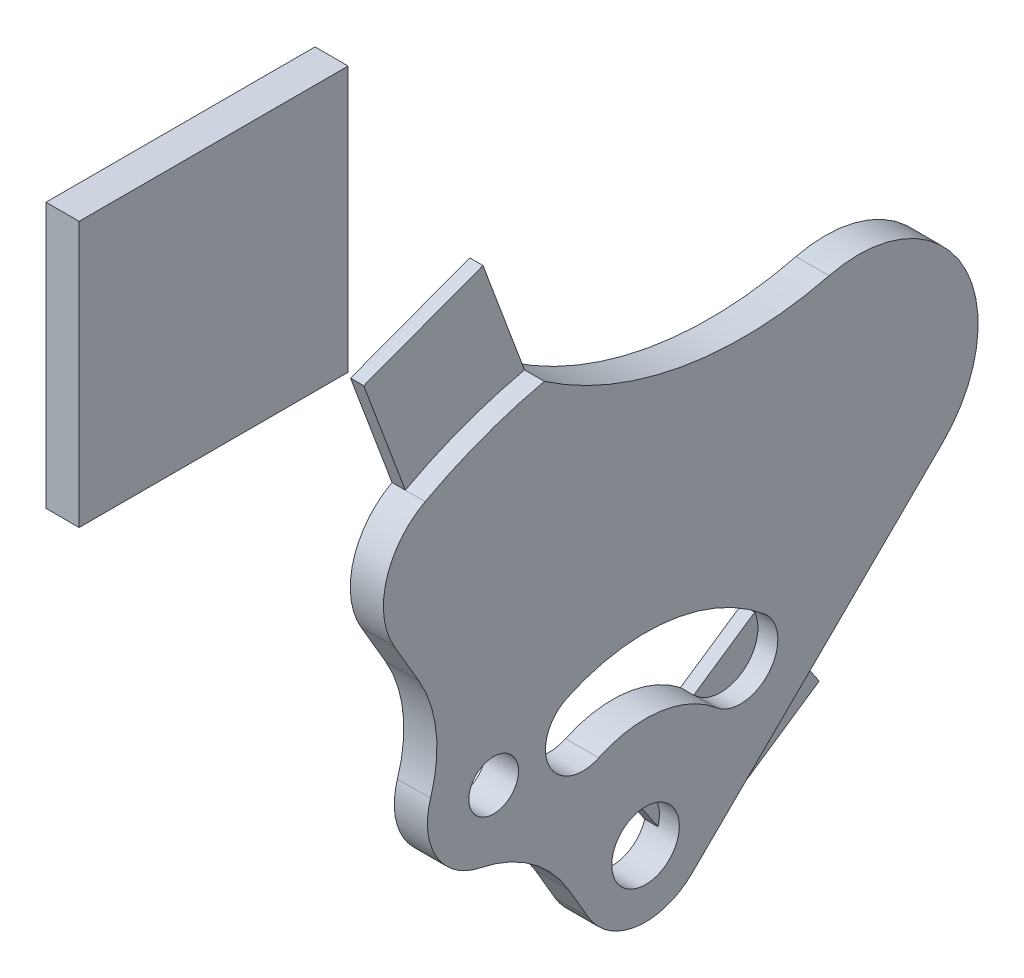
SolidWorks part; units mm, degrees
material "PC High Viscosity"
ref_plane "Front Plane" through (0, 0, 0) normal (0, 0, 1) x (1, 0, 0)
ref_plane "Top Plane" through (0, 0, 0) normal (0, 1, 0) x (1, 0, 0)
ref_plane "Right Plane" through (0, 0, 0) normal (1, 0, 0) x (0, 0, -1)
sketch "Sketch4" plane through (0, 0, 0) normal (1, 0, 0) x (0, 0, -1)
  line L0 (-2.9914, -1.0639) -> (-130.6611, 357.9089) construction
  line L1 (2.9914, 1.0639) -> (-124.6782, 360.0367) construction
  line L2 (-124.6782, 360.0367) -> (-130.6611, 357.9089) construction
  line L3 (-130.6611, 357.9089) -> (-133.6525, 356.845) construction
  line L4 (-133.6525, 356.845) -> (-184.7204, 500.4341) construction
  line L5 (-184.7204, 500.4341) -> (-172.7547, 504.6897) construction
  line L6 (-172.7547, 504.6897) -> (-121.6868, 361.1006) construction
  line L7 (-121.6868, 361.1006) -> (-124.6782, 360.0367) construction
  line L16 (-186.8468, 405.2616) -> (-158.2054, 369.0306)
  line L25 (-177.3558, 422.8765) -> (-158.2054, 369.0306) construction
  line L28 (-159.4072, 429.26) -> (-140.2567, 375.4141) construction
  line L29 (-140.2567, 375.4141) -> (-158.2054, 369.0306) construction
  line L30 (-177.3558, 422.8765) -> (-159.4072, 429.26) construction
  line L32 (32.4045, -6.3458) -> (174.3086, 718.2843) construction
  line L33 (174.3086, 718.2843) -> (227.2775, 707.9114) construction
  line L34 (227.2775, 707.9114) -> (85.3734, -16.7186) construction
  line L35 (85.3734, -16.7186) -> (32.4045, -6.3458) construction
  line L36 (0, 0) -> (32.4045, -6.3458) construction
  line L37 (-674.4124, -1612.5949) -> (1608.6068, -1612.5949) construction
  line L42 (-403.8007, 406.7051) -> (-222.8257, 406.7051) construction
  line L43 (-197.4257, 432.1051) -> (-403.8007, 432.1051) construction
  line L44 (-197.4257, 432.1051) -> (-197.4257, 381.3051) construction
  line L45 (-197.4257, 381.3051) -> (-403.8007, 381.3051) construction
  line L46 (-403.8007, 432.1051) -> (-403.8007, 381.3051) construction
  line L47 (-222.8257, 406.7051) -> (-222.8257, 432.1051) construction
  line L48 (-222.8257, 406.7051) -> (-222.8257, 381.3051) construction
  line L49 (-222.8257, 406.7051) -> (-197.4257, 406.7051) construction
  line L50 (-403.8007, 381.3051) -> (-403.8007, -1612.5949) construction
  line L51 (-251.4007, -1612.5949) -> (-251.4007, -1434.7949) construction
  line L52 (-251.4007, -1434.7949) -> (-168.8507, -1434.7949) construction
  line L53 (-168.8507, -1434.7949) -> (-168.8507, -1612.5949) construction
  line L54 (-186.8468, 405.2616) -> (-172.8601, 410.236) construction
  line L55 (-177.3558, 422.8765) -> (-175.6535, 418.0902)
  line L56 (-175.6535, 418.0902) -> (-157.7049, 424.4737)
  line L57 (-157.7049, 424.4737) -> (-140.2567, 375.4141)
  line L58 (-181.6115, 434.8423) -> (-163.6628, 441.2258) construction
  line L59 (-163.6628, 441.2258) -> (-131.2987, 452.7362) construction
  line L60 (-131.2987, 452.7362) -> (26.3813, 9.3826) construction
  line L61 (26.3813, 9.3826) -> (2.9914, 1.0639) construction
  line L63 (-186.8468, 405.2616) -> (-198.9147, 420.5273)
  line L65 (-246.6871, 397.9992) -> (-226.2306, 341.9309)
  line L66 (-237.676, 336.5464) -> (-264.4742, 382.3241)
  line L67 (-223.6051, 0) -> (0, 0) construction
  line L68 (0, 0) -> (0, 470.5586) construction
  line L70 (-158.2054, 369.0306) -> (-140.2567, 375.4141)
  circle A0 centre (0, 0) radius 3.175 construction
  arc A2 (-246.6871, 397.9992) -> (-222.8257, 432.1051) centre (-222.8257, 406.7051) cw
  arc A17 (-222.8257, 432.1051) -> (-198.9147, 420.5273) centre (-222.8257, 401.6251) cw
  arc A19 (-264.4742, 382.3241) -> (-177.3558, 422.8765) centre (-222.8257, 406.7051) cw
  circle A20 centre (-222.8257, 406.7051) radius 25.4 construction
  circle A21 centre (-222.8257, 411.0231) radius 21.082 construction
  arc A23 (-226.2306, 341.9309) -> (-237.676, 336.5464) centre (-232.196, 339.7544) cw
  circle A24 centre (-232.196, 339.7544) radius 44.45 construction
  dimension "D1" = 6.35
  dimension "D9" = 5.08
  dimension "D10" = 5.08
  dimension "D13" = 11.08
  dimension "D19" = 2044.7
  dimension "D18" = 50.8
  dimension "D7" = 42.164
  dimension "D5" = 57.15
  dimension "D17" = 1612.5949
  dimension "D20" = 50.8
  dimension "D22" = 82.55
  dimension "D23" = 177.8
  dimension "D24" = 152.4
  dimension "D25" = 251.4007
  dimension "D6" = 69.85
  dimension "D27" = 31.75
  dimension "D12" = 19.05
  dimension "D8" = 48.26
  dimension "D11" = 17.78
  dimension "D26" = 6.35
  dimension "D16" = 6.35
  dimension "D2" = 152.4
  dimension "D3" = 12.7
  dimension "D4" = 381
  dimension "D14" = 33.02
  dimension "D15" = 53.975
  dimension "D21" = 206.375
extrude "Boss-Extrude2" add sketch "Sketch4" along normal mid plane 38.1
sketch "Sketch5" plane through (0, 377.5419, 134.2738) normal (0, -0.9422, -0.3351) x (-1, 0, 0)
  line L0 (-19.05, -6.35) -> (-9.525, -6.35) construction
  line L9 (-19.05, -6.35) -> (19.05, -6.35) construction
  line L10 (-9.525, -6.35) -> (9.525, -6.35) construction
  line L11 (9.525, -6.35) -> (19.05, -6.35) construction
  line L12 (-19.05, -25.4) -> (-19.05, -6.35) construction
  line L13 (19.05, -25.4) -> (19.05, -6.35) construction
  line L15 (-19.05, -25.4) -> (-8.89, -19.05)
  line L18 (19.05, -25.4) -> (19.05, -6.35) construction
  line L28 (8.89, -19.05) -> (19.05, -25.4)
  line L30 (-19.05, -46.4997) -> (-19.05, -25.4) construction
  line L32 (-19.05, -25.4) -> (-19.05, -6.35)
  line L33 (-19.05, -6.35) -> (19.05, -6.35)
  line L34 (19.05, -6.35) -> (19.05, -25.4)
  line L39 (-8.89, -19.05) -> (8.89, -19.05)
  circle A0 centre (-9.525, -6.35) radius 3.175 construction
  circle A1 centre (9.525, -6.35) radius 3.175 construction
  dimension "D2" = 12.7
  dimension "D3" = 6.35
  dimension "D1" = 19.05
  dimension "D4" = 17.78
  dimension "D5" = 6.35
  dimension "D6" = 19.05
sketch "Sketch9" plane through (0, 426.6015, 151.722) normal (0, 0.9422, 0.3351) x (1, 0, 0)
  line L0 (0, -6.35) -> (0, -25.4) construction
  line L1 (19.05, -6.35) -> (-19.05, -6.35) construction
  line L2 (19.05, -25.4) -> (-19.05, -25.4) construction
  line L4 (8.89, -19.05) -> (-8.89, -19.05) construction
  circle A0 centre (6.35, -19.05) radius 3.2385
  circle A1 centre (-9.525, -6.35) radius 3.175
  circle A4 centre (9.525, -6.35) radius 3.175
  circle A6 centre (9.525, -6.35) radius 3.175 construction
  circle A7 centre (-9.525, -6.35) radius 3.175 construction
  dimension "D1" = 6.477
  dimension "D2" = 6.35
extrude "Cut-Extrude4" cut sketch "Sketch9" against normal through all
sketch "Sketch12" plane through (19.05, 0, 0) normal (1, 0, 0) x (0, 0, -1)
  line L0 (-233.8882, 379.4995) -> (-227.7504, 377.8715) construction
  line L1 (-238.1338, 369.0584) -> (-227.7504, 377.8715) construction
  line L2 (-236.9571, 380.3135) -> (-233.8882, 379.4995) construction
  line L3 (-233.8882, 379.4995) -> (-230.8193, 378.6855) construction
  circle A2 centre (-230.8193, 378.6855) radius 1.5875
  circle A5 centre (-227.7504, 377.8715) radius 1.5875 construction
  circle A6 centre (-233.8882, 379.4995) radius 1.5875 construction
  circle A7 centre (-236.9571, 380.3135) radius 1.5875
  dimension "D1" = 3.175
  dimension "D4" = 13.6193
extrude "Cut-Extrude5" [suppressed] cut sketch "Sketch12" against normal through all
sketch "Sketch29" plane through (19.05, 0, 0) normal (1, 0, 0) x (0, 0, -1)
  line L0 (-250.3738, 382.2602) -> (-232.196, 339.7544) construction
  line L1 (-246.6871, 397.9992) -> (-226.2306, 341.9309) construction
  line L2 (-237.676, 336.5464) -> (-264.4742, 382.3241) construction
  line L3 (-237.676, 336.5464) -> (-264.4742, 382.3241)
  line L4 (-246.6871, 397.9992) -> (-226.2306, 341.9309)
  arc A1 (-241.8244, 389.8465) -> (-258.9232, 374.6739) centre (-250.3738, 382.2602) ccw
  arc A3 (-177.3558, 422.8765) -> (-264.4742, 382.3241) centre (-222.8257, 406.7051) ccw construction
  arc A4 (-237.676, 336.5464) -> (-226.2306, 341.9309) centre (-232.196, 339.7544) ccw construction
  arc A5 (-222.8257, 432.1051) -> (-246.6871, 397.9992) centre (-222.8257, 406.7051) ccw construction
  arc A6 (-258.9232, 374.6739) -> (-264.4742, 382.3241) centre (-222.8257, 406.7051) ccw
  arc A7 (-241.8244, 389.8465) -> (-246.6871, 397.9992) centre (-222.8257, 406.7051) ccw
  circle A8 centre (-250.3738, 382.2602) radius 3.175 construction
  arc A9 (-237.676, 336.5464) -> (-226.2306, 341.9309) centre (-232.196, 339.7544) ccw
  dimension "D1" = 46.2296
  dimension "D2" = 6.35
sketch "Sketch15" plane through (0, 426.6015, 151.722) normal (0, 0.9422, 0.3351) x (1, 0, 0)
  line L5 (-3.175, -9.392) -> (-3.175, -9.525) construction
  line L6 (-3.175, -9.525) -> (6.35, -9.525)
  line L7 (6.35, -9.525) -> (6.35, -6.35) construction
  line L9 (9.525, -6.35) -> (9.525, -9.525)
  line L10 (9.525, -9.525) -> (6.35, -9.525)
  line L11 (-3.175, -9.525) -> (-9.525, -9.525)
  line L12 (-9.525, -9.525) -> (-9.525, -6.35)
  line L13 (-9.525, -6.35) -> (9.525, -6.35)
  circle A0 centre (9.525, -6.35) radius 3.175 construction
  circle A1 centre (9.525, -6.35) radius 3.175 construction
extrude "Cut-Extrude7" cut sketch "Sketch15" against normal up to surface (52.07 mm away) up to face at (6.35, 370.0733, 155.2737)
sketch "Sketch16" plane through (0, 426.6015, 151.722) normal (0, 0.9422, 0.3351) x (1, 0, 0)
  line L0 (19.05, -6.35) -> (19.05, -25.4) construction
  line L1 (12.7, -6.35) -> (19.05, -6.35)
  line L2 (12.7, -6.35) -> (12.7, 3.175)
  line L3 (12.7, 3.175) -> (19.05, 3.175)
  line L4 (19.05, -6.35) -> (19.05, 3.175)
  line L6 (-19.05, -6.35) -> (-12.7, -6.35)
  line L7 (-19.05, -6.35) -> (-19.05, 3.175)
  line L8 (-19.05, 3.175) -> (-12.7, 3.175)
  line L9 (-12.7, -6.35) -> (-12.7, 3.175)
  dimension "D1" = 9.525
extrude "Boss-Extrude3" add sketch "Sketch16" against normal up to surface (52.07 mm away) up to face at (6.35, 370.0733, 155.2737)
sketch "Sketch20" plane through (19.05, 0, 0) normal (1, 0, 0) x (0, 0, -1)
  line L1 (-148.7306, 427.6655) -> (-175.6535, 418.0902)
  line L2 (-177.3558, 422.8765) -> (-175.6535, 418.0902)
  line L3 (-227.0055, 454.7837) -> (-160.4336, 460.5713)
  line L4 (-160.4336, 460.5713) -> (-148.7306, 427.6655)
  line L5 (-131.2824, 378.6059) -> (-148.7306, 427.6655) construction
  line L6 (-170.2399, 459.7188) -> (-157.7049, 424.4737) construction
  arc A0 (-177.3558, 422.8765) -> (-264.4742, 382.3241) centre (-222.8257, 406.7051) ccw construction
  arc A2 (-227.0055, 454.7837) -> (-177.3558, 422.8765) centre (-222.8257, 406.7051) cw
  dimension "D1" = 9.525
  dimension "D2" = 34.925
extrude "Boss-Extrude5" add sketch "Sketch20" against normal up to surface (38.1 mm away) up to face at (-19.05, 398.1168, 201.4005)
sketch "Sketch21" plane through (0, 426.6015, 151.722) normal (0, -0.9422, -0.3351) x (1, 0, 0)
  line L2 (-19.05, -3.175) -> (-19.05, 25.4) construction
  line L4 (19.05, 14.478) -> (19.05, 6.35)
  line L12 (0, 19.05) -> (0, 6.35) construction
  line L13 (0, 6.35) -> (9.525, 6.35) construction
  line L14 (-9.525, 6.35) -> (0, 6.35) construction
  line L16 (19.05, 6.35) -> (19.05, -3.175)
  line L18 (-19.05, 6.35) -> (-19.05, -3.175)
  line L19 (-19.05, -3.175) -> (-12.7, -3.175) construction
  line L20 (7.62, 24.765) -> (15.3353, 14.478) construction
  line L21 (15.9703, 14.478) -> (19.05, 14.478)
  line L26 (-19.05, -3.175) -> (19.05, -3.175)
  line L27 (-19.05, 14.478) -> (-19.05, 6.35)
  line L28 (0, 19.05) -> (6.35, 19.05) construction
  line L29 (-7.62, 24.765) -> (-15.3353, 14.478) construction
  line L30 (-15.9703, 14.478) -> (-19.05, 14.478)
  line L31 (-14.491, 14.478) -> (14.491, 14.478) construction
  line L32 (8.0264, 25.0698) -> (15.9703, 14.478)
  line L33 (19.05, 25.4) -> (19.05, -3.175) construction
  line L34 (-8.0264, 25.0698) -> (-15.9703, 14.478)
  arc A0 (7.62, 24.765) -> (-7.62, 24.765) centre (0, 19.05) ccw construction
  circle A1 centre (9.525, 6.35) radius 3.175 construction
  circle A2 centre (-9.525, 6.35) radius 3.175 construction
  circle A4 centre (9.525, 6.35) radius 9.525 construction
  circle A5 centre (-9.525, 6.35) radius 9.525 construction
  arc A6 (14.491, 14.478) -> (19.05, 6.35) centre (9.525, 6.35) cw construction
  arc A7 (-14.491, 14.478) -> (-19.05, 6.35) centre (-9.525, 6.35) ccw construction
  circle A10 centre (0, 19.05) radius 10.033 construction
  circle A11 centre (6.35, 19.05) radius 3.2385 construction
  circle A12 centre (6.35, 19.05) radius 3.2385 construction
  arc A13 (-8.0264, 25.0698) -> (8.0264, 25.0698) centre (0, 19.05) cw
  dimension "D1" = 9.525
  dimension "D2" = 12.7
  dimension "D4" = 38.1
  dimension "D5" = 17.653
  dimension "D6" = 6.35
  dimension "D7" = 0.508
  dimension "D3" = 9.525
extrude "Cut-Extrude10" cut sketch "Sketch21" against normal through all
sketch "Sketch22" plane through (19.05, 0, 0) normal (1, 0, 0) x (0, 0, -1)
  line L0 (-250.3738, 382.2602) -> (-253.0021, 402.4135) construction
  line L1 (-253.0021, 402.4135) -> (-248.3687, 390.0742) construction
  line L2 (-239.4905, 381.1842) -> (-219.7422, 376.3814) construction
  circle A3 centre (-250.3738, 382.2602) radius 3.175 construction
  circle A5 centre (-250.3738, 382.2602) radius 3.175 construction
  circle A6 centre (-253.0021, 402.4135) radius 3.175
  arc A7 (-251.0294, 388.3418) -> (-256.1454, 401.9664) centre (-222.8257, 406.7051) ccw construction
  arc A8 (-247.999, 384.3675) -> (-256.1454, 401.9664) centre (-222.8257, 406.7051) ccw construction
  arc A9 (-241.8244, 389.8465) -> (-246.6871, 397.9992) centre (-222.8257, 406.7051) ccw construction
  circle A10 centre (-253.0021, 402.4135) radius 3.175 construction
  circle A11 centre (-248.3687, 390.0742) radius 3.175 construction
  arc A12 (-256.1454, 401.9664) -> (-251.0294, 388.3418) centre (-222.8257, 406.7051) ccw construction
  arc A13 (-256.1454, 401.9664) -> (-251.0294, 388.3418) centre (-222.8257, 406.7051) ccw construction
  circle A14 centre (-239.4905, 381.1842) radius 3.175
  circle A15 centre (-219.7422, 376.3814) radius 3.175 construction
  arc A16 (-241.2264, 378.5257) -> (-219.421, 373.2227) centre (-222.8257, 406.7051) ccw construction
  arc A17 (-241.2264, 378.5257) -> (-219.421, 373.2227) centre (-222.8257, 406.7051) ccw construction
  dimension "D2" = 2.54
extrude "Cut-Extrude11" cut sketch "Sketch22" against normal through all
sketch "Sketch27" plane through (-17.1704, -4.3152, 12.1333) normal (0.8, 0.2011, -0.5653) x (-0.5432, -0.1573, -0.8247)
  line L0 (-201.4256, 405.6346) -> (-205.4694, 414.2586) construction
  line L1 (-223.978, 441.7649) -> (-206.025, 403.4779) construction
  line L3 (-196.8261, 407.7913) -> (-200.2757, 406.1738) construction
  line L4 (-210.0688, 412.1019) -> (-205.4694, 414.2586) construction
  line L6 (-205.4694, 414.2586) -> (-198.0815, 417.7228) construction
  line L7 (-210.8186, 444.8862) -> (-194.0377, 409.0988) construction
  line L8 (-200.2757, 406.1738) -> (-213.0622, 400.1781) construction
  circle A0 centre (-205.4694, 414.2586) radius 6.35
  dimension "D1" = 12.7
  dimension "D2" = 9.525
  dimension "D3" = 5.08
extrude "Cut-Extrude13" cut sketch "Sketch27" against normal blind 5.08 and the other way blind 3.175
sketch "Sketch28" plane through (0, -4.8514, 13.641) normal (0, 0.3351, -0.9422) x (-1, 0, 0)
  line L1 (-19.05, 484.5286) -> (-6.35, 484.5286)
  line L2 (-19.05, 484.5286) -> (-19.05, 478.1786)
  line L3 (-19.05, 478.1786) -> (-6.35, 478.1786)
  line L4 (-6.35, 484.5286) -> (-6.35, 478.1786)
  line L5 (-12.7, 452.7786) -> (-19.05, 452.7786) construction
  line L9 (-19.05, 492.305) -> (-19.05, 452.7786) construction
  dimension "D1" = 12.7
  dimension "D2" = 31.75
  dimension "D3" = 6.35
extrude "Cut-Extrude14" cut sketch "Sketch28" against normal blind 6.35
sketch "Sketch30" plane through (0, 1.0639, -2.9914) normal (0, 0.3351, -0.9422) x (-1, 0, 0)
  line L0 (12.7, 400.7086) -> (12.7, 452.7786) construction
  line L1 (-19.05, 443.2536) -> (-12.7, 443.2536)
  line L2 (-19.05, 443.2536) -> (-19.05, 422.9336)
  line L3 (-19.05, 422.9336) -> (-12.7, 422.9336)
  line L4 (-12.7, 443.2536) -> (-12.7, 422.9336)
  line L6 (-12.7, 400.7086) -> (-19.05, 400.7086) construction
  line L8 (12.7, 443.2536) -> (19.05, 443.2536)
  line L9 (12.7, 443.2536) -> (12.7, 422.9336)
  line L10 (12.7, 422.9336) -> (19.05, 422.9336)
  line L11 (19.05, 443.2536) -> (19.05, 422.9336)
  line L12 (19.05, 452.7786) -> (12.7, 452.7786) construction
  line L13 (-12.7, 400.7086) -> (-12.7, 452.7786) construction
  line L14 (-12.7, 452.7786) -> (-12.7, 400.7086) construction
  dimension "D1" = 6.35
  dimension "D2" = 22.225
  dimension "D4" = 9.525
sketch "Sketch31" plane through (-19.05, 0, 0) normal (-1, 0, 0) x (0, 0, 1)
  line L0 (145.5388, 418.6911) -> (138.7298, 399.5459) construction
  line L1 (177.6708, 403.8935) -> (195.3097, 377.494) construction
  line L2 (170.6506, 380.1104) -> (186.4902, 390.6938) construction
  line L4 (165.363, 421.7501) -> (148.7306, 427.6655) construction
  line L5 (174.479, 394.9192) -> (177.6708, 403.8935) construction
  line L6 (177.6708, 403.8935) -> (154.3219, 412.1976) construction
  line L8 (198.9147, 420.5273) -> (158.2054, 369.0306) construction
  circle A0 centre (177.6708, 403.8935) radius 3.175
  circle A1 centre (174.479, 394.9192) radius 3.175 construction
  circle A2 centre (226.7616, 415.3788) radius 15.875 construction
  arc A5 (246.6871, 397.9992) -> (222.8257, 432.1051) centre (222.8257, 406.7051) ccw construction
  circle A6 centre (177.6708, 403.8935) radius 8.5635 construction
  circle A7 centre (195.3097, 377.494) radius 3.175 construction
  circle A8 centre (195.3097, 377.494) radius 6.35 construction
  circle A9 centre (170.6506, 380.1104) radius 2.7249 construction
  dimension "D1" = 9.525
  dimension "D2" = 3.175
  dimension "D3" = 6.35
  dimension "D5" = 31.75
  dimension "D4" = 12.7
  dimension "D6" = 6.35
  dimension "D8" = 19.05
  dimension "D7" = 31.75
  dimension "D9" = 12.7
sketch "Sketch33" plane through (0, 0, 0) normal (1, 0, 0) x (0, 0, -1)
  line L0 (-199.2473, 457.1969) -> (-212.0786, 429.7194)
  line L1 (-212.0786, 429.7194) -> (-222.8257, 406.7051) construction
  line L3 (-222.8257, 406.7051) -> (-227.0055, 454.7837) construction
  line L4 (-227.0055, 454.7837) -> (-199.2473, 457.1969)
  line L5 (-178.6079, 458.9913) -> (-227.0055, 454.7837) construction
  line L9 (-237.676, 336.5464) -> (-264.4742, 382.3241) construction
  line L10 (-237.676, 336.5464) -> (-264.4742, 382.3241)
  line L11 (-246.6871, 397.9992) -> (-226.2306, 341.9309) construction
  line L12 (-246.6871, 397.9992) -> (-226.2306, 341.9309)
  arc A0 (-227.0055, 454.7837) -> (-264.4742, 382.3241) centre (-222.8257, 406.7051) ccw construction
  arc A1 (-222.8257, 432.1051) -> (-246.6871, 397.9992) centre (-222.8257, 406.7051) ccw construction
  arc A2 (-212.0786, 429.7194) -> (-246.6871, 397.9992) centre (-222.8257, 406.7051) ccw
  arc A3 (-227.0055, 454.7837) -> (-264.4742, 382.3241) centre (-222.8257, 406.7051) ccw
  arc A6 (-237.676, 336.5464) -> (-226.2306, 341.9309) centre (-232.196, 339.7544) ccw construction
  arc A7 (-237.676, 336.5464) -> (-226.2306, 341.9309) centre (-232.196, 339.7544) ccw
  dimension "D1" = 30
extrude "Cut-Extrude18" cut sketch "Sketch33" against normal mid plane 50.8
sketch "Sketch48" plane through (0, 377.5419, 134.2738) normal (0, -0.9422, -0.3351) x (1, 0, 0)
  line L0 (9.525, 9.525) -> (-9.525, 9.525) construction
  line L1 (-2.3813, 55.5406) -> (2.3812, 55.5406)
  line L2 (-2.3813, 55.5406) -> (-2.3812, 9.525)
  line L3 (-2.3812, 9.525) -> (2.3812, 9.525)
  line L4 (2.3812, 55.5406) -> (2.3812, 9.525)
  line L8 (19.05, 55.5406) -> (-19.05, 55.5406) construction
  line L10 (0, 9.525) -> (0, 0) construction
  dimension "D1" = 4.7625
extrude "Cut-Extrude23" cut sketch "Sketch48" against normal up to surface (102.2996 mm away)
sketch "Sketch35" plane through (0, 0, 0) normal (1, 0, 0) x (0, 0, -1)
  line L0 (-202.4062, 450.4323) -> (-212.0786, 429.7194) construction
  line L1 (-212.0786, 429.7194) -> (-222.8257, 406.7051) construction
  line L3 (-178.6079, 458.9913) -> (-199.2473, 457.1969) construction
  line L4 (-204.6452, 456.7277) -> (-202.4062, 450.4323) construction
  line L5 (-178.6079, 458.9913) -> (-176.0021, 451.6645) construction
  line L6 (-199.2473, 457.1969) -> (-211.9088, 430.083) construction
  line L7 (-237.676, 336.5464) -> (-264.4742, 382.3241) construction
  line L8 (-237.676, 336.5464) -> (-264.4742, 382.3241)
  line L9 (-198.9147, 420.5273) -> (-178.0852, 361.9603) construction
  line L10 (-204.6452, 456.7277) -> (-195.7642, 457.4997)
  line L11 (-246.6871, 397.9992) -> (-226.2306, 341.9309)
  line L13 (-204.6452, 456.7277) -> (-195.7642, 457.4997) construction
  line L17 (-198.9147, 420.5273) -> (-158.2054, 369.0306) construction
  line L18 (-198.9147, 420.5273) -> (-189.0698, 408.0736)
  line L21 (-178.0852, 361.9603) -> (-158.2054, 369.0306) construction
  line L22 (-199.2473, 457.1969) -> (-193.349, 457.7097) construction
  line L24 (-158.2054, 369.0306) -> (-143.2482, 374.3502) construction
  line L25 (-187.4365, 446.9653) -> (-172.2286, 427.7275)
  line L27 (-226.0532, 454.857) -> (-204.6452, 456.7277)
  line L28 (-195.7642, 457.4997) -> (-187.4365, 446.9653)
  line L31 (-198.9147, 420.5273) -> (-158.2054, 369.0306) construction
  line L32 (-198.9147, 420.5273) -> (-226.0532, 454.857) construction
  line L34 (-189.0698, 408.0736) -> (-172.2286, 427.7275)
  line L35 (-172.2286, 427.7275) -> (-192.1545, 411.9757) construction
  arc A0 (-177.3558, 422.8765) -> (-264.4742, 382.3241) centre (-222.8257, 406.7051) ccw construction
  arc A2 (-222.8257, 432.1051) -> (-246.6871, 397.9992) centre (-222.8257, 406.7051) ccw construction
  arc A8 (-226.0532, 454.857) -> (-264.4742, 382.3241) centre (-222.8257, 406.7051) ccw
  arc A16 (-237.676, 336.5464) -> (-226.2306, 341.9309) centre (-232.196, 339.7544) ccw construction
  arc A17 (-237.676, 336.5464) -> (-226.2306, 341.9309) centre (-232.196, 339.7544) ccw
  arc A18 (-198.9147, 420.5273) -> (-222.8257, 432.1051) centre (-222.8257, 401.6251) ccw construction
  arc A19 (-198.9147, 420.5273) -> (-222.8257, 432.1051) centre (-222.8257, 401.6251) ccw
  arc A20 (-222.8257, 432.1051) -> (-246.6871, 397.9992) centre (-222.8257, 406.7051) ccw
  dimension "D1" = 25.4
  dimension "D2" = 15.875
  dimension "D3" = 11.08
extrude "Boss-Extrude6" add sketch "Sketch35" along normal mid plane 4.7625 separate body
sketch "Sketch41" plane through (2.3813, 0, 0) normal (1, 0, 0) x (0, 0, -1)
  line L0 (-259.9018, 374.5134) -> (-237.676, 336.5464)
  line L5 (-232.196, 339.7544) -> (-222.8257, 411.0231) construction
  line L6 (-238.2055, 352.5203) -> (-223.0908, 350.5331) construction
  line L7 (-246.3049, 339.6051) -> (-238.2055, 352.5203) construction
  line L8 (-223.0908, 350.5331) -> (-213.5213, 349.2749) construction
  line L9 (-238.2055, 352.5203) -> (-233.0776, 360.6973) construction
  line L10 (-246.6871, 397.9992) -> (-226.2306, 341.9309) construction
  line L13 (-227.7336, 335.2367) -> (-203.7343, 358.942)
  line L14 (-264.4742, 382.3241) -> (-237.676, 336.5464) construction
  line L17 (-198.9147, 420.5273) -> (-158.2054, 369.0306) construction
  arc A0 (-238.2055, 352.5203) -> (-223.0908, 350.5331) centre (-232.196, 339.7544) cw construction
  circle A3 centre (-232.196, 339.7544) radius 44.45 construction
  arc A13 (-237.676, 336.5464) -> (-227.7336, 335.2367) centre (-232.196, 339.7544) ccw
  arc A16 (-237.676, 336.5464) -> (-226.2306, 341.9309) centre (-232.196, 339.7544) ccw construction
  arc A23 (-220.783, 353.2651) -> (-239.7287, 355.7561) centre (-232.196, 339.7544) ccw
  arc A24 (-241.89, 383.1344) -> (-214.6031, 378.257) centre (-222.8257, 411.0231) ccw
  arc A25 (-225.3987, 347.8011) -> (-236.6823, 349.2846) centre (-232.196, 339.7544) ccw
  arc A26 (-222.8257, 432.1051) -> (-246.6871, 397.9992) centre (-222.8257, 406.7051) ccw construction
  arc A27 (-241.89, 383.1344) -> (-259.9018, 374.5134) centre (-232.196, 339.7544) ccw construction
  arc A28 (-225.3987, 347.8011) -> (-220.783, 353.2651) centre (-223.0908, 350.5331) ccw
  arc A29 (-239.7287, 355.7561) -> (-236.6823, 349.2846) centre (-238.2055, 352.5203) ccw
  arc A30 (-238.2055, 352.5203) -> (-246.3049, 339.6051) centre (-232.196, 339.7544) ccw construction
  arc A31 (-239.7287, 355.7561) -> (-249.881, 339.5673) centre (-232.196, 339.7544) ccw construction
  arc A32 (-236.6823, 349.2846) -> (-242.7288, 339.643) centre (-232.196, 339.7544) ccw construction
  arc A33 (-236.6823, 349.2846) -> (-239.7287, 355.7561) centre (-238.2055, 352.5203) ccw construction
  arc A34 (-249.881, 339.5673) -> (-242.7288, 339.643) centre (-246.3049, 339.6051) ccw construction
  circle A35 centre (-232.196, 339.7544) radius 1.651
  arc A38 (-259.9018, 374.5134) -> (-241.89, 383.1344) centre (-232.196, 339.7544) cw
  arc A39 (-203.7343, 358.942) -> (-214.6031, 378.257) centre (-211.8071, 367.1149) ccw
  point P1 (-230.3567, 353.7437)
  point P30 (-244.1496, 347.2507)
  dimension "D1" = 12.7
  dimension "D2" = 3.5763
  dimension "D3" = 3.302
  dimension "D6" = 7.62
  dimension "D5" = 31.75
  dimension "D4" = 14.1097
extrude "Boss-Extrude9" add sketch "Sketch41" along normal blind 3.175 from offset 6.35 separate body
hole_wizard "#8 Clearance Hole1" positions "Sketch43" profile "Sketch44" hole size "#8" standard "ANSI Inch" end condition through all
sketch "Sketch43" plane through (2.3813, 0, 0) normal (1, 0, 0) x (0, 0, -1)
  arc A3 (-239.7287, 355.7561) -> (-236.6823, 349.2846) centre (-238.2055, 352.5203) ccw construction
  point P0 (-238.2055, 352.5203)
  point P10 (-232.196, 339.7544)
sketch "Sketch44" plane through (2.3813, 352.5203, 238.2055) normal (0, 1, 0) x (0, 0, -1)
  line L0 (0, 0) -> (0, 21.4313)
  line L1 (0, 21.4313) -> (2.1526, 21.4313)
  line L2 (2.1526, 21.4313) -> (2.1526, 0)
  line L5 (2.1526, 0) -> (0, 0)
  line L11 (0, -6.35) -> (0, 107.95) construction
  dimension "Thru Hole Dia." = 4.3053
  dimension "Thru Hole Depth" = 21.4313
mirror "Mirror1" about plane through (0, 0, 0) normal (1, 0, 0) of bodies 145
sketch "Sketch54" [suppressed] plane through (-11.9062, 0, 0) normal (-1, 0, 0) x (0, 0, 1)
  circle A0 centre (232.196, 339.7544) radius 3.2385
  dimension "D1" = 6.477
extrude "Cut-Extrude29" cut sketch "Sketch54" against normal through all
sketch "Sketch68" plane through (11.9062, 0, 0) normal (1, 0, 0) x (0, 0, -1)
  line L0 (-259.9018, 374.5134) -> (-237.676, 336.5464) construction
  line L1 (-249.9577, 357.5264) -> (-243.5417, 346.5663)
  arc A0 (-249.9577, 357.5264) -> (-243.5417, 346.5663) centre (-246.7497, 352.0464) ccw
  circle A1 centre (-232.196, 339.7544) radius 2.1526 construction
  dimension "D1" = 12.7
  dimension "D2" = 19.05
extrude "Boss-Extrude17" add sketch "Sketch68" against normal up to surface (3.175 mm away) up to face at (8.7312, 339.7544, 228.9575)
sketch "Sketch47" plane through (11.9062, 0, 0) normal (1, 0, 0) x (0, 0, -1)
  circle A0 centre (-246.7497, 352.0464) radius 2.3813
  arc A2 (-249.9577, 357.5264) -> (-243.5417, 346.5663) centre (-246.7497, 352.0464) ccw construction
  dimension "D1" = 4.7625
extrude "Cut-Extrude22" cut sketch "Sketch47" against normal through all
fillet "Fillet10" radius 12.7 2 edges at (10.3187, 346.5663, 243.5417) (10.3187, 357.5264, 249.9577)
fillet "Fillet11" radius 7.62 1 edges at (10.3187, 374.5134, 259.9018)
sketch "Sketch56" plane through (-2.3813, 0, 0) normal (-1, 0, 0) x (0, 0, 1)
  line L2 (198.9147, 420.5273) -> (158.2054, 369.0306) construction
  line L3 (143.3775, 379.4383) -> (157.5661, 368.2219) construction
  line L4 (172.2286, 427.7275) -> (189.0698, 408.0736)
  line L5 (172.2286, 427.7275) -> (137.6402, 383.9738)
  line L6 (150.0939, 374.1289) -> (189.0698, 408.0736)
  line L7 (189.0698, 408.0736) -> (157.5661, 368.2219) construction
  line L8 (172.2286, 427.7275) -> (195.7642, 457.4997) construction
  line L11 (150.0939, 374.1289) -> (137.6402, 383.9738)
  dimension "D1" = 50.8
  dimension "D2" = 9.525
extrude "Boss-Extrude10" add sketch "Sketch56" against normal up to surface (4.7625 mm away) up to face at (2.3813, 352.5203, 236.0529)
sketch "Sketch57" plane through (-2.3813, 0, 0) normal (-1, 0, 0) x (0, 0, 1)
  line L0 (137.6402, 383.9738) -> (150.0939, 374.1289) construction
  line L4 (137.6402, 383.9738) -> (195.7642, 457.4997) construction
  line L6 (142.6143, 379.1916) -> (137.2267, 383.4506) construction
  line L68 (172.2286, 427.7275) -> (192.1545, 411.9757) construction
  line L69 (172.2286, 427.7275) -> (192.1545, 411.9757) construction
  circle A0 centre (154.3666, 389.7733) radius 3.175
  dimension "D1" = 6.35
  dimension "D3" = 14.9225
  dimension "D2" = 6.35
extrude "Cut-Extrude31" cut sketch "Sketch57" against normal through all
sketch "Sketch58" plane through (2.3813, 0, 0) normal (1, 0, 0) x (0, 0, -1)
  circle A0 centre (-251.0885, 393.6914) radius 3.175
  circle A1 centre (-232.196, 339.7544) radius 2.1526 construction
  arc A4 (-222.8257, 432.1051) -> (-246.6871, 397.9992) centre (-222.8257, 406.7051) ccw construction
  dimension "D1" = 6.35
  dimension "D2" = 2.54
  dimension "D3" = 57.15
extrude "Cut-Extrude32" cut sketch "Sketch58" against normal through all
sketch "Sketch60" plane through (-2.3813, 0, 0) normal (-1, 0, 0) x (0, 0, 1)
  line L0 (238.1613, 337.5779) -> (232.7202, 322.6645)
  line L1 (220.7895, 327.0175) -> (226.2306, 341.9309)
  line L4 (226.2306, 341.9309) -> (246.6871, 397.9992) construction
  circle A0 centre (232.196, 339.7544) radius 6.35 construction
  arc A1 (232.7202, 322.6645) -> (220.7895, 327.0175) centre (226.7548, 324.841) cw
  arc A2 (226.2306, 341.9309) -> (237.676, 336.5464) centre (232.196, 339.7544) ccw construction
  arc A3 (238.1613, 337.5779) -> (226.2306, 341.9309) centre (232.196, 339.7544) cw
  dimension "D1" = 15.875
extrude "Boss-Extrude12" add sketch "Sketch60" against normal up to surface (4.7625 mm away) contours L1 A3 L0 A1
fillet "Fillet4" radius 161.925 1 edges at (0, 337.0403, 237.9652)
sketch "Sketch61" plane through (-2.3813, 0, 0) normal (-1, 0, 0) x (0, 0, 1)
  line L0 (157.33, 408.8811) -> (149.4541, 398.9182)
  line L1 (157.33, 408.8811) -> (159.8208, 406.9121)
  line L3 (159.8208, 406.9121) -> (152.7795, 398.005)
  line L4 (137.6402, 383.9738) -> (195.7642, 457.4997) construction
  line L5 (155.124, 413.0533) -> (158.5114, 410.3755) construction
  line L7 (137.6402, 383.9738) -> (195.7642, 457.4997) construction
  line L8 (152.7795, 398.005) -> (151.9448, 396.9492) construction
  line L9 (151.9448, 396.9492) -> (149.4541, 398.9182) construction
  line L10 (137.6402, 383.9738) -> (150.0939, 374.1289) construction
  circle A0 centre (155.124, 413.0533) radius 1.5875 construction
  arc A3 (149.4541, 398.9182) -> (152.7795, 398.005) centre (155.124, 413.0533) ccw
  dimension "D4" = 14.605
  dimension "D6" = 3.175
  dimension "D2" = 3.175
  dimension "D1" = 12.7
  dimension "D3" = 19.05
  dimension "D5" = 4.318
extrude "Cut-Extrude33" cut sketch "Sketch61" against normal through all
hole_wizard "#10 (0.1935) Diameter Hole1" positions "Sketch62" profile "Sketch63" hole size "#10" standard "ANSI Inch" end condition through all
sketch "Sketch62" plane through (-2.3813, 0, 0) normal (-1, 0, 0) x (0, 0, 1)
  line L0 (200.2439, 447.8073) -> (212.6976, 437.9624) construction
  line L1 (198.9147, 420.5273) -> (189.0698, 408.0736) construction
  line L4 (159.8208, 406.9121) -> (157.33, 408.8811) construction
  line L5 (157.33, 408.8811) -> (195.7642, 457.4997) construction
  point P0 (200.2439, 447.8073)
  dimension "D1" = 9.525
  dimension "D2" = 57.15
sketch "Sketch63" plane through (-2.3813, 447.8073, 200.2439) normal (0, 1, 0) x (0, 0, 1)
  line L0 (0, 0) -> (0, 21.4313)
  line L1 (0, 21.4313) -> (2.4574, 21.4313)
  line L2 (2.4574, 21.4313) -> (2.4574, 0)
  line L5 (2.4574, 0) -> (0, 0)
  line L11 (0, -6.35) -> (0, 107.95) construction
  dimension "Thru Hole Dia." = 4.9149
  dimension "Thru Hole Depth" = 21.4313
fillet "Fillet6" radius 1.27 1 edges at (0, 408.8811, 157.33)
fillet "Fillet7" radius 2 2 edges at (0, 406.9121, 159.8208) (0, 398.005, 152.7795)
fillet "Fillet9" radius 12.7 1 edges at (0, 457.4997, 195.7642)
fillet "Fillet8" radius 6.35 2 edges at (0, 374.1289, 150.0939) (0, 383.9738, 137.6402)
delete or keep bodies "Body-Delete/Keep 2" type keep bodies bodies 205
delete or keep bodies "Body-Delete/Keep 1" [suppressed] type keep bodies bodies 197
sketch "Sketch64" [suppressed] plane through (-2.3813, 0, 0) normal (-1, 0, 0) x (0, 0, 1)
  line L0 (177.8155, 434.7949) -> (187.2666, 446.7504)
  line L1 (177.8155, 434.7949) -> (175.6628, 436.4967)
  line L2 (187.2666, 446.7504) -> (185.1139, 448.4522)
  line L3 (175.6628, 436.4967) -> (185.1139, 448.4522)
  line L4 (158.1176, 409.8774) -> (191.5198, 452.1306) construction
  line L5 (162.9027, 385.2843) -> (174.3952, 395.2933)
  line L6 (162.9027, 385.2843) -> (176.7942, 369.3337)
  line L7 (174.3952, 395.2933) -> (188.2867, 379.3427)
  line L8 (176.7942, 369.3337) -> (188.2867, 379.3427)
  line L9 (154.068, 377.59) -> (189.0698, 408.0736) construction
  line L10 (229.6902, 351.4131) -> (224.4667, 337.0962)
  line L11 (229.6902, 351.4131) -> (215.0041, 356.7713)
  line L12 (224.4667, 337.0962) -> (209.7806, 342.4545)
  line L13 (215.0041, 356.7713) -> (209.7806, 342.4545)
  line L14 (220.7895, 327.0175) -> (246.6871, 397.9992) construction
  line L15 (265.7687, 428.726) -> (274.1248, 431.4514)
  line L16 (274.1248, 431.4514) -> (278.8504, 416.9625)
  line L17 (278.8504, 416.9625) -> (270.4943, 414.2372)
  line L18 (265.7687, 428.726) -> (270.4943, 414.2372) construction
  arc A0 (264.4742, 382.3241) -> (226.0532, 454.857) centre (222.8257, 406.7051) ccw construction
  arc A1 (265.7687, 428.726) -> (270.4943, 414.2372) centre (222.8257, 406.7051) cw
  line M15 (154.068, 377.59) -> (189.0698, 408.0736)
  line M19 (246.6871, 397.9992) -> (220.7895, 327.0175)
  line M27 (191.5198, 452.1306) -> (158.1176, 409.8774)
  dimension "D1" = 15.24
extrude "Boss-Extrude13" [suppressed] add sketch "Sketch64" against normal blind 1.27 contours L11 L13 L12 M19 | L6 L8 L7 M15 | L3 L1 L2 M27 | L15 L16 L17 A1
sketch "Sketch65" [suppressed] plane through (2.3813, 0, 0) normal (1, 0, 0) x (0, 0, -1)
  line L1 (-129.2814, 530.595) -> (-84.9636, 530.595)
  line L2 (-129.2814, 530.595) -> (-129.2814, 486.2771)
  line L3 (-129.2814, 486.2771) -> (-84.9636, 486.2771)
  line L4 (-84.9636, 530.595) -> (-84.9636, 486.2771)
extrude "Boss-Extrude14" [suppressed] add sketch "Sketch65" against normal up to surface (4.7625 mm away) separate body
sketch "Sketch66" plane through (8.7312, 0, 0) normal (-1, 0, 0) x (0, 0, 1)
  line L5 (219.6761, 352.0886) -> (232.293, 343.5403)
  line L6 (219.6761, 352.0886) -> (213.6432, 343.1843)
  line L7 (232.293, 343.5403) -> (226.26, 334.636)
  line L8 (213.6432, 343.1843) -> (226.26, 334.636)
  line L11 (241.89, 383.1344) -> (253.316, 378.8664)
  line L12 (241.89, 383.1344) -> (245.8692, 393.7869)
  line L13 (253.316, 378.8664) -> (257.2951, 389.5189)
  line L14 (245.8692, 393.7869) -> (257.2951, 389.5189)
  arc A1 (253.316, 378.8664) -> (241.89, 383.1344) centre (232.196, 339.7544) ccw construction
  dimension "D1" = 15.24
extrude "Boss-Extrude15" add sketch "Sketch66" against normal blind 1.27
sketch "Sketch67" plane through (8.7312, 0, 0) normal (-1, 0, 0) x (0, 0, 1)
  line L1 (260.6944, 418.7095) -> (286.4783, 418.7095)
  line L2 (260.6944, 418.7095) -> (260.6944, 393.294)
  line L3 (260.6944, 393.294) -> (286.4783, 393.294)
  line L4 (286.4783, 418.7095) -> (286.4783, 393.294)
extrude "Boss-Extrude16" add sketch "Sketch67" against normal up to surface (3.175 mm away) separate body up to face at (11.9062, 352.0464, 244.3684)
